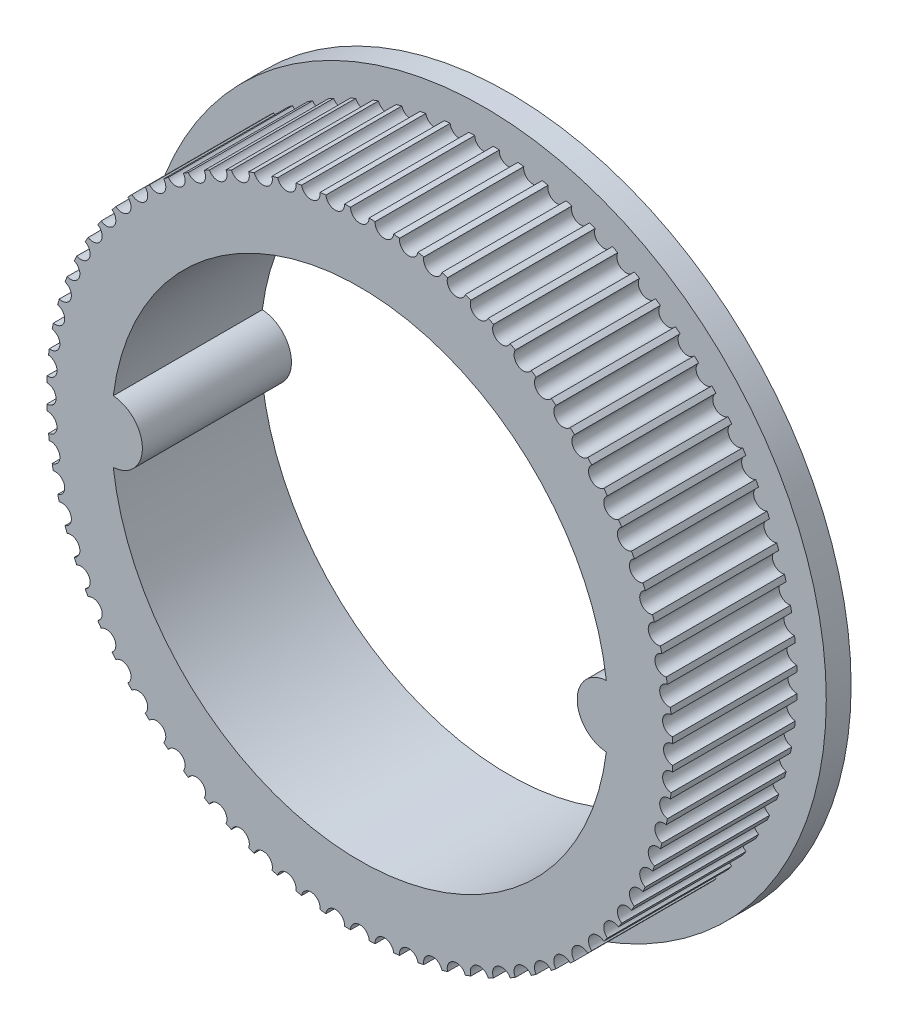
SolidWorks part; units mm, degrees
ref_plane "Alzado" through (0, 0, 0) normal (0, 0, 1) x (1, 0, 0)
ref_plane "Planta" through (0, 0, 0) normal (0, 1, 0) x (1, 0, 0)
ref_plane "Vista lateral" through (0, 0, 0) normal (1, 0, 0) x (0, 0, -1)
sketch "Croquis1" plane through (0, 0, 0) normal (0, 0, 1) x (1, 0, 0)
  circle A0 centre (0, 0) radius 27.55
  dimension "D1" = 55.1
extrude "Saliente-Extruir1" add sketch "Croquis1" along normal blind 2
sketch "Croquis2" plane through (0, 0, 2) normal (0, 0, 1) x (1, 0, 0)
  circle A0 centre (0, 0) radius 25.2
  dimension "D1" = 50.4
extrude "Saliente-Extruir2" add sketch "Croquis2" along normal blind 10
sketch "Croquis3" plane through (0, 0, 12) normal (0, 0, 1) x (1, 0, 0)
  circle A0 centre (0, 0) radius 20
  dimension "D1" = 40
extrude "Cortar-Extruir1" cut sketch "Croquis3" against normal through all
sketch "Croquis4" plane through (0, 0, 0) normal (0, 0, 1) x (1, 0, 0)
  line L0 (-27.55, 0) -> (27.55, 0) construction
  circle A0 centre (20, 0) radius 2.5
  circle A1 centre (0, 0) radius 20 construction
  circle A2 centre (-20, 0) radius 2.5
  circle A3 centre (0, 0) radius 27.55 construction
  dimension "D1" = 5
  dimension "D2" = 5
extrude "Saliente-Extruir3" add sketch "Croquis4" along normal blind 12
sketch "Croquis5" plane through (0, 0, 12) normal (0, 0, 1) x (1, 0, 0)
  line L0 (0, 0) -> (25.2, 0) construction
  circle A0 centre (0, 0) radius 25.2 construction
  circle A1 centre (25.2, 0) radius 0.75
  circle A2 centre (25.1223, -1.9772) radius 0.75
  circle A3 centre (24.8897, -3.9421) radius 0.75
  circle A4 centre (24.5037, -5.8828) radius 0.75
  circle A5 centre (23.9666, -7.7872) radius 0.75
  circle A6 centre (23.2818, -9.6436) radius 0.75
  circle A7 centre (22.4534, -11.4406) radius 0.75
  circle A8 centre (21.4865, -13.167) radius 0.75
  circle A9 centre (20.3872, -14.8122) radius 0.75
  circle A10 centre (19.1622, -16.3661) radius 0.75
  circle A11 centre (17.8191, -17.8191) radius 0.75
  circle A12 centre (16.3661, -19.1622) radius 0.75
  circle A13 centre (14.8122, -20.3872) radius 0.75
  circle A14 centre (13.167, -21.4865) radius 0.75
  circle A15 centre (11.4406, -22.4534) radius 0.75
  circle A16 centre (9.6436, -23.2818) radius 0.75
  circle A17 centre (7.7872, -23.9666) radius 0.75
  circle A18 centre (5.8828, -24.5037) radius 0.75
  circle A19 centre (3.9421, -24.8897) radius 0.75
  circle A20 centre (1.9772, -25.1223) radius 0.75
  circle A21 centre (0, -25.2) radius 0.75
  circle A22 centre (-1.9772, -25.1223) radius 0.75
  circle A23 centre (-3.9421, -24.8897) radius 0.75
  circle A24 centre (-5.8828, -24.5037) radius 0.75
  circle A25 centre (-7.7872, -23.9666) radius 0.75
  circle A26 centre (-9.6436, -23.2818) radius 0.75
  circle A27 centre (-11.4406, -22.4534) radius 0.75
  circle A28 centre (-13.167, -21.4865) radius 0.75
  circle A29 centre (-14.8122, -20.3872) radius 0.75
  circle A30 centre (-16.3661, -19.1622) radius 0.75
  circle A31 centre (-17.8191, -17.8191) radius 0.75
  circle A32 centre (-19.1622, -16.3661) radius 0.75
  circle A33 centre (-20.3872, -14.8122) radius 0.75
  circle A34 centre (-21.4865, -13.167) radius 0.75
  circle A35 centre (-22.4534, -11.4406) radius 0.75
  circle A36 centre (-23.2818, -9.6436) radius 0.75
  circle A37 centre (-23.9666, -7.7872) radius 0.75
  circle A38 centre (-24.5037, -5.8828) radius 0.75
  circle A39 centre (-24.8897, -3.9421) radius 0.75
  circle A40 centre (-25.1223, -1.9772) radius 0.75
  circle A41 centre (-25.2, 0) radius 0.75
  circle A42 centre (-25.1223, 1.9772) radius 0.75
  circle A43 centre (-24.8897, 3.9421) radius 0.75
  circle A44 centre (-24.5037, 5.8828) radius 0.75
  circle A45 centre (-23.9666, 7.7872) radius 0.75
  circle A46 centre (-23.2818, 9.6436) radius 0.75
  circle A47 centre (-22.4534, 11.4406) radius 0.75
  circle A48 centre (-21.4865, 13.167) radius 0.75
  circle A49 centre (-20.3872, 14.8122) radius 0.75
  circle A50 centre (-19.1622, 16.3661) radius 0.75
  circle A51 centre (-17.8191, 17.8191) radius 0.75
  circle A52 centre (-16.3661, 19.1622) radius 0.75
  circle A53 centre (-14.8122, 20.3872) radius 0.75
  circle A54 centre (-13.167, 21.4865) radius 0.75
  circle A55 centre (-11.4406, 22.4534) radius 0.75
  circle A56 centre (-9.6436, 23.2818) radius 0.75
  circle A57 centre (-7.7872, 23.9666) radius 0.75
  circle A58 centre (-5.8828, 24.5037) radius 0.75
  circle A59 centre (-3.9421, 24.8897) radius 0.75
  circle A60 centre (-1.9772, 25.1223) radius 0.75
  circle A61 centre (0, 25.2) radius 0.75
  circle A62 centre (1.9772, 25.1223) radius 0.75
  circle A63 centre (3.9421, 24.8897) radius 0.75
  circle A64 centre (5.8828, 24.5037) radius 0.75
  circle A65 centre (7.7872, 23.9666) radius 0.75
  circle A66 centre (9.6436, 23.2818) radius 0.75
  circle A67 centre (11.4406, 22.4534) radius 0.75
  circle A68 centre (13.167, 21.4865) radius 0.75
  circle A69 centre (14.8122, 20.3872) radius 0.75
  circle A70 centre (16.3661, 19.1622) radius 0.75
  circle A71 centre (17.8191, 17.8191) radius 0.75
  circle A72 centre (19.1622, 16.3661) radius 0.75
  circle A73 centre (20.3872, 14.8122) radius 0.75
  circle A74 centre (21.4865, 13.167) radius 0.75
  circle A75 centre (22.4534, 11.4406) radius 0.75
  circle A76 centre (23.2818, 9.6436) radius 0.75
  circle A77 centre (23.9666, 7.7872) radius 0.75
  circle A78 centre (24.5037, 5.8828) radius 0.75
  circle A79 centre (24.8897, 3.9421) radius 0.75
  circle A80 centre (25.1223, 1.9772) radius 0.75
  point P168 (0, 0)
  dimension "D1" = 1.5
  dimension "D2" = 80
extrude "Cortar-Extruir2" cut sketch "Croquis5" against normal blind 10
